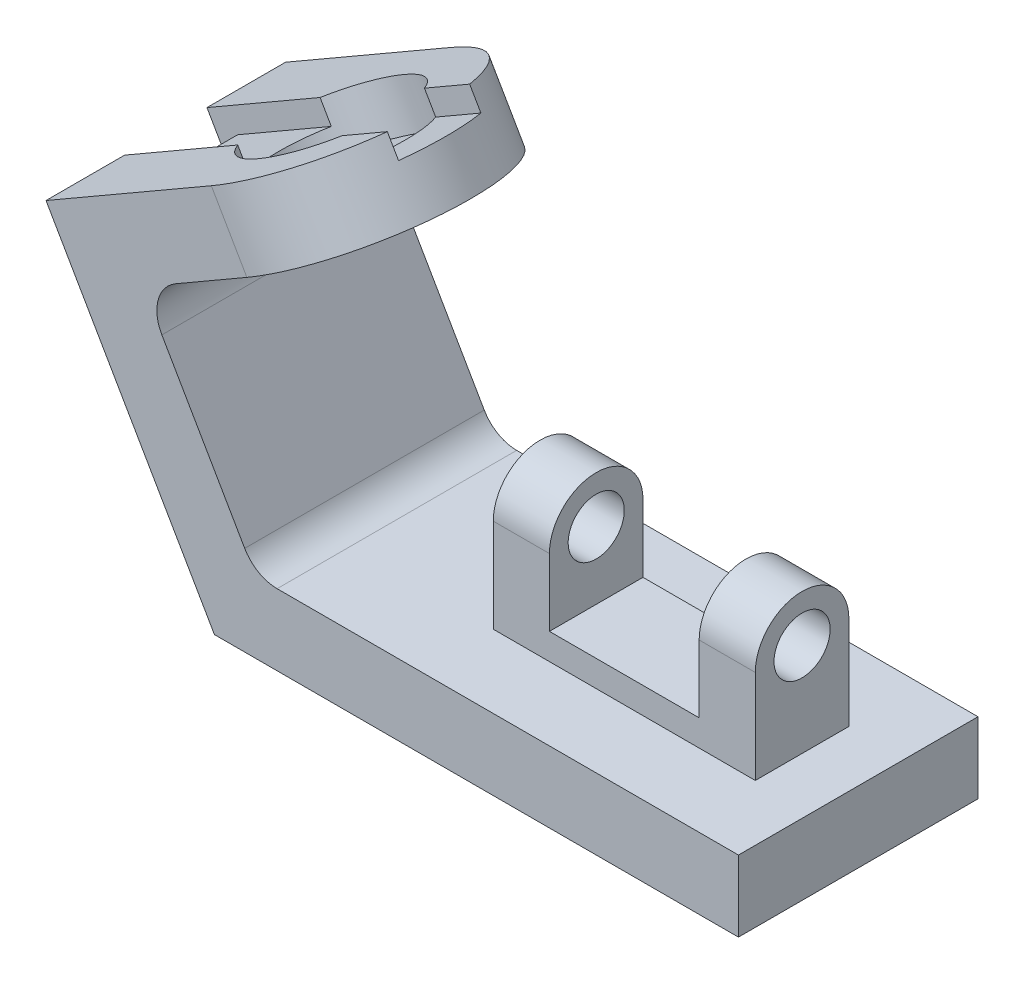
SolidWorks part; units mm, degrees
material "Laiton"
ref_plane "Plan de face" through (0, 0, 0) normal (0, 0, 1) x (1, 0, 0)
ref_plane "Plan de dessus" through (0, 0, 0) normal (0, 1, 0) x (1, 0, 0)
ref_plane "Plan de droite" through (0, 0, 0) normal (1, 0, 0) x (0, 0, -1)
sketch "Esquisse1" plane through (0, 0, 0) normal (0, 0, 1) x (1, 0, 0)
  line L0 (0, 0) -> (140, 0) construction
  line L1 (0, 0) -> (-45, 77.9423)
  line L2 (-45, 77.9423) -> (-0.8327, 103.4423)
  line L3 (-0.8327, 103.4423) -> (8.6673, 86.9878)
  line L4 (8.6673, 86.9878) -> (-19.0455, 70.9878)
  line L5 (-19.0455, 70.9878) -> (10.9697, 19)
  line L6 (10.9697, 19) -> (140, 19)
  line L7 (140, 19) -> (140, 0)
  line L8 (140, 0) -> (0, 0)
  dimension "D1" = 140
  dimension "D2" = 60
  dimension "D3" = 19
  dimension "D4" = 19
  dimension "D5" = 19
  dimension "D6" = 90
  dimension "D7" = 51
extrude "Boss.-Extru.1" add sketch "Esquisse1" against normal blind 64
sketch "Esquisse2" plane through (-45, 77.9423, 0) normal (-0.5, 0.866, 0) x (0.866, 0.5, 0)
  line L0 (130.7436, 0) -> (19, 0) construction
  line L1 (51, 64) -> (51, 0)
  arc A0 (51, 64) -> (51, 0) centre (51, 32) cw
  dimension "D1" = 32
extrude "Boss.-Extru.2" add sketch "Esquisse2" against normal blind 19
sketch "Esquisse3" plane through (-45, 77.9423, 0) normal (-0.5, 0.866, 0) x (0.866, 0.5, 0)
  circle A0 centre (51, 32) radius 9.5
  dimension "D1" = 19
extrude "Enlèv. mat.-Extru.1" cut sketch "Esquisse3" against normal up to next
sketch "Esquisse4" plane through (-45, 77.9423, 0) normal (-0.5, 0.866, 0) x (0.866, 0.5, 0)
  line L0 (0, 32) -> (95.651, 32) construction
  line L1 (0, 64) -> (0, 0) construction
  line L3 (0, 43) -> (81.05, 43)
  line L4 (0, 43) -> (0, 21)
  line L5 (0, 21) -> (81.05, 21)
  line L7 (0, 43) -> (81.05, 21) construction
  line L8 (0, 21) -> (81.05, 43) construction
  arc A0 (51, 0) -> (51, 64) centre (51, 32) ccw construction
  arc A1 (81.05, 21) -> (81.05, 43) centre (51, 32) ccw
  point P4 (40.525, 32)
  point P9 (0, 0)
  dimension "D1" = 22
extrude "Enlèv. mat.-Extru.2" cut sketch "Esquisse4" against normal blind 6
sketch "Esquisse5" plane through (-45, 77.9423, 0) normal (-0.5, 0.866, 0) x (0.866, 0.5, 0)
  circle A0 centre (51, 32) radius 19.5
  dimension "D1" = 39
extrude "Enlèv. mat.-Extru.3" cut sketch "Esquisse5" against normal blind 12
sketch "Esquisse6" plane through (0, 0, 0) normal (-0.866, -0.5, 0) x (0, 0, 1)
  line L0 (-32, 0) -> (-32, 107.7621) construction
  line L1 (-64, 0) -> (0, 0) construction
  line L3 (-43, 90) -> (-21, 90)
  line L4 (-43, 90) -> (-43, 34)
  line L5 (-43, 34) -> (-21, 34)
  line L6 (-21, 90) -> (-21, 34)
  line L7 (-43, 90) -> (-21, 34) construction
  line L8 (-43, 34) -> (-21, 90) construction
  point P4 (-32, 62)
  point P9 (0, 0)
  dimension "D1" = 56
extrude "Enlèv. mat.-Extru.4" cut sketch "Esquisse6" against normal blind 6
ref_plane "Plan2" through (125, 0, 0) normal (1, 0, 0) x (0, 0, -1)
sketch "Esquisse8" plane through (125, 0, 0) normal (1, 0, 0) x (0, 0, -1)
  line L0 (19.5, 19) -> (19.5, 44)
  line L1 (64, 19) -> (0, 19) construction
  line L2 (44.5, 44) -> (44.5, 19)
  line L3 (44.5, 19) -> (19.5, 19)
  line L4 (0, 0) -> (0, 19) construction
  arc A0 (19.5, 44) -> (44.5, 44) centre (32, 44) cw
  point P6 (32, 19)
  dimension "D1" = 32
  dimension "D2" = 25
  dimension "D3" = 25
extrude "Boss.-Extru.3" add sketch "Esquisse8" against normal blind 70
sketch "Esquisse9" plane through (0, 0, -19.5) normal (0, 0, 1) x (1, 0, 0)
  line L0 (125, 56.5) -> (55, 56.5) construction
  line L1 (70, 26) -> (110, 26)
  line L2 (70, 26) -> (70, 56.5)
  line L3 (70, 56.5) -> (110, 56.5)
  line L4 (110, 26) -> (110, 56.5)
  line L5 (90, 19) -> (90, 76.7556) construction
  line L6 (55, 19) -> (125, 19) construction
  dimension "D1" = 40
  dimension "D2" = 7
extrude "Enlèv. mat.-Extru.5" cut sketch "Esquisse9" against normal through all
sketch "Esquisse10" plane through (55, 0, 0) normal (-1, 0, 0) x (0, 0, 1)
  circle A0 centre (-32, 44) radius 7.5
  dimension "D1" = 15
extrude "Enlèv. mat.-Extru.6" cut sketch "Esquisse10" against normal through all
fillet "Congé1" radius 10 2 edges at (-19.0455, 70.9878, -32) (10.9697, 19, -32)
equation "\"A\"= 60deg"
equation "\"B\"= 64"
equation "\"C\"= 140"
equation "\"D\"= 19"
equation "\"D1@Esquisse1\"=\"C\""
equation "\"D2@Esquisse1\"=\"A\""
equation "\"D3@Esquisse1\"=\"D\""
equation "\"D4@Esquisse1\"=\"D\""
equation "\"D5@Esquisse1\"=\"D\""
equation "\"D1@Boss.-Extru.1\"=\"B\""
equation "\"D1@Esquisse2\"=\"B\" / 2"
equation "\"D1@Boss.-Extru.2\"=\"D\""
equation "\"D1@Esquisse8\"=\"B\" / 2"
equation "\"E\"= 25"
equation "\"D2@Esquisse8\"=\"E\""
equation "\"D3@Esquisse8\"=\"E\""
